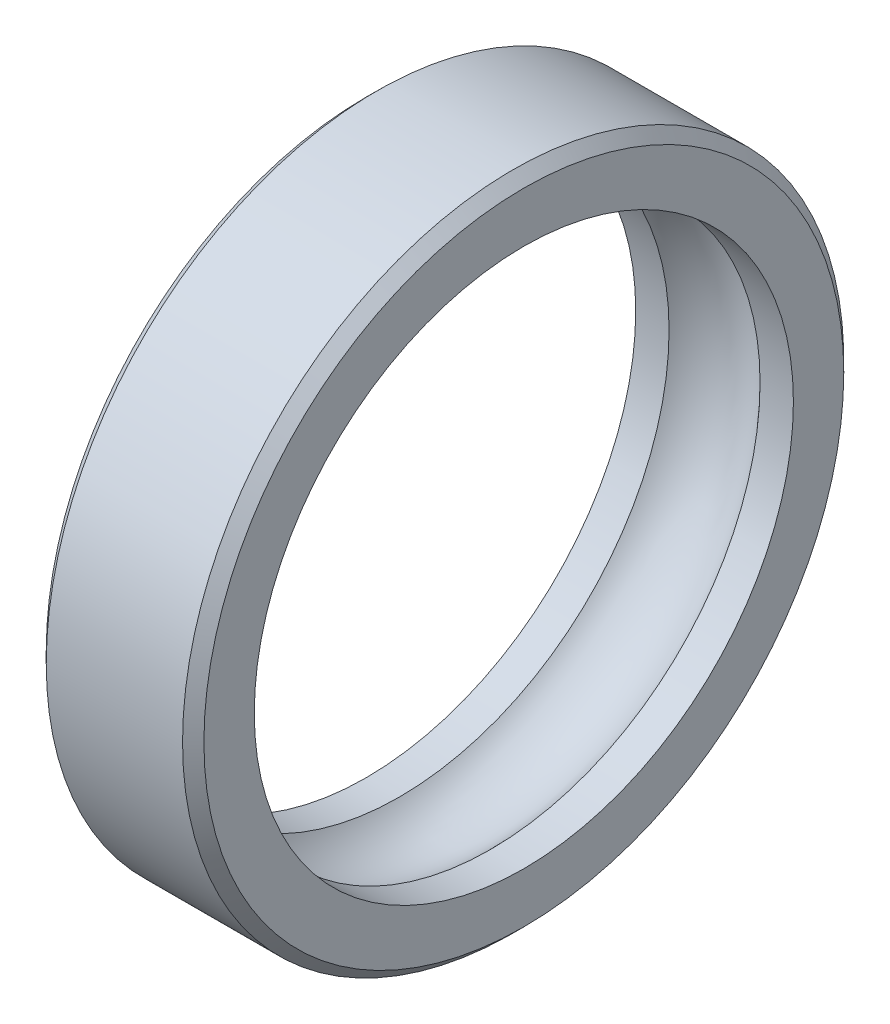
SolidWorks part; units mm, degrees
ref_plane "Front Plane" through (0, 0, 0) normal (0, 0, 1) x (1, 0, 0)
ref_plane "Top Plane" through (0, 0, 0) normal (0, 1, 0) x (1, 0, 0)
ref_plane "Right Plane" through (0, 0, 0) normal (1, 0, 0) x (0, 0, -1)
sketch "Sketch1" plane through (0, 0, 0) normal (0, 0, 1) x (1, 0, 0)
  line L0 (-15.0201, 0) -> (15.0201, 0) construction
  line L1 (0, 59) -> (0, 57) construction
  line L2 (-15.5, 65) -> (15.5, 65)
  line L3 (-15.5, 65) -> (-15.5, 53)
  line L4 (-15.5, 53) -> (-8.9443, 53)
  line L5 (15.5, 65) -> (15.5, 53)
  line L6 (-15.5, 65) -> (15.5, 53) construction
  line L7 (-15.5, 53) -> (15.5, 65) construction
  line L8 (8.9443, 53) -> (15.5, 53)
  line L9 (0, 53) -> (0, 0) construction
  arc A0 (8.9443, 53) -> (-8.9443, 53) centre (0, 45) ccw
  point P0 (0, 59)
  point P4 (0, 0)
  dimension "D5" = 12
  dimension "D1" = 31
  dimension "D2" = 53
  dimension "D3" = 65
  dimension "D4" = 8
revolve "Revolve1" add sketch "Sketch1" angle 360 about L0
chamfer "Chamfer1" distance 2.1 angle 45 2 edges at (15.5, 0, 65) (-15.5, 0, 65)
